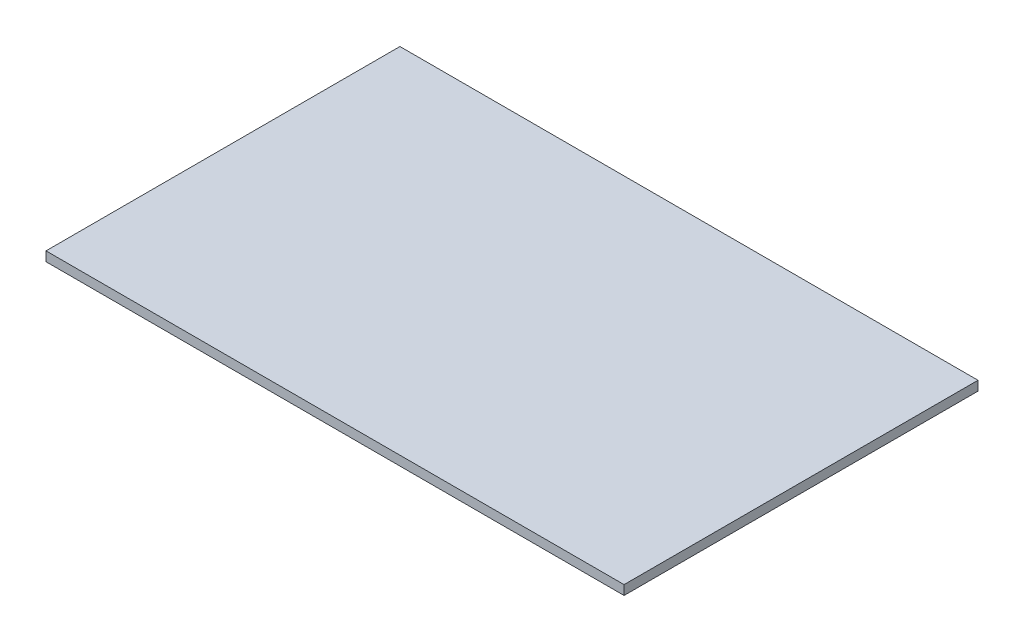
SolidWorks part; units mm, degrees
ref_plane "Front Plane" through (0, 0, 0) normal (0, 0, 1) x (1, 0, 0)
ref_plane "Top Plane" through (0, 0, 0) normal (0, 1, 0) x (1, 0, 0)
ref_plane "Right Plane" through (0, 0, 0) normal (1, 0, 0) x (0, 0, -1)
sketch "Sketch2" plane through (0, 0, 0) normal (0, 1, 0) x (1, 0, 0)
  line L1 (122.5, 75) -> (-122.5, 75)
  line L2 (122.5, 75) -> (122.5, -75)
  line L3 (122.5, -75) -> (-122.5, -75)
  line L4 (-122.5, 75) -> (-122.5, -75)
  line L5 (122.5, 75) -> (-122.5, -75) construction
  line L6 (122.5, -75) -> (-122.5, 75) construction
  point P0 (0, 0)
  dimension "D1" = 245
  dimension "D2" = 150
extrude "Boss-Extrude1" add sketch "Sketch2" along normal blind 4
